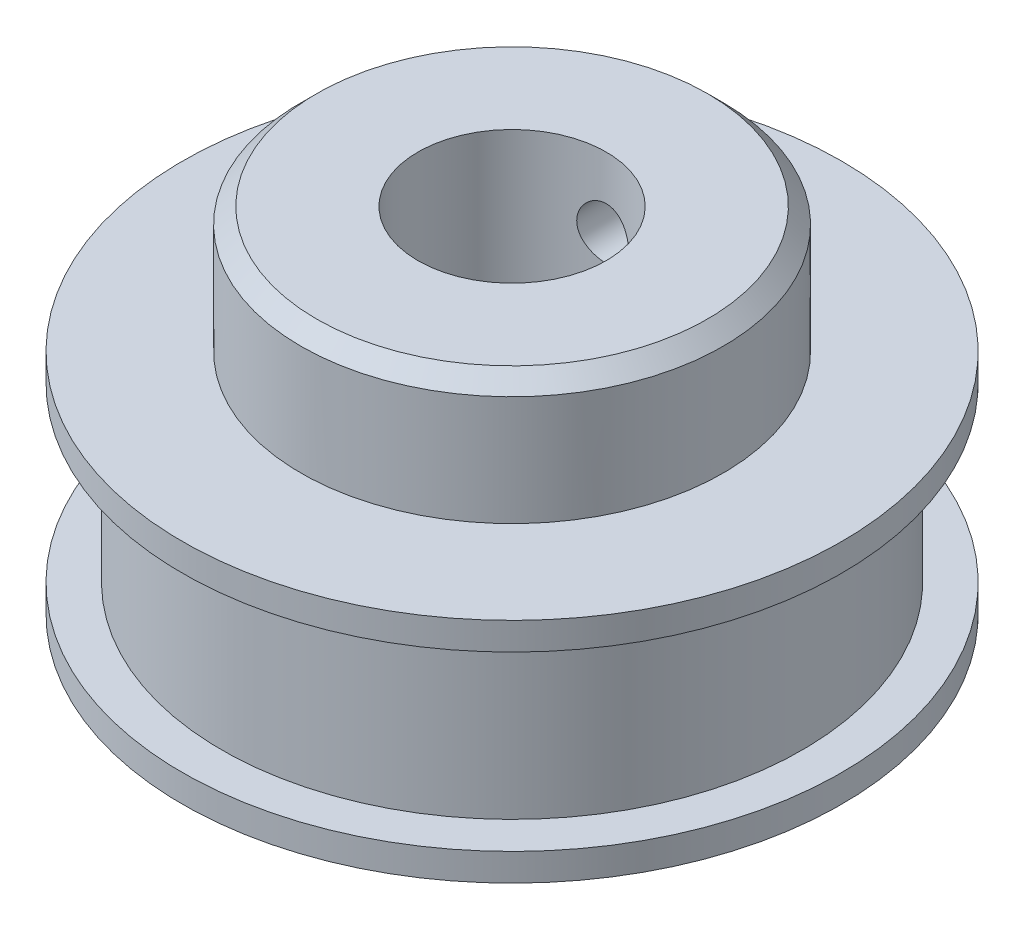
SolidWorks part; units mm, degrees
ref_plane "Piano frontale" through (0, 0, 0) normal (0, 0, 1) x (1, 0, 0)
ref_plane "Piano superiore" through (0, 0, 0) normal (0, 1, 0) x (1, 0, 0)
ref_plane "Piano destro" through (0, 0, 0) normal (1, 0, 0) x (0, 0, -1)
sketch "Schizzo1" plane through (0, 0, 0) normal (0, 0, 1) x (1, 0, 0)
  line L0 (0, 11.25) -> (13.45, 11.25)
  line L1 (13.45, 11.25) -> (13.45, 3.25)
  line L2 (13.45, 3.25) -> (21, 3.25)
  line L3 (21, 3.25) -> (21, 1.5)
  line L4 (21, 1.5) -> (18.5, 1.5)
  line L5 (18.5, 1.5) -> (18.5, -9.5)
  line L6 (18.5, -9.5) -> (21, -9.5)
  line L7 (21, -9.5) -> (21, -11.25)
  line L8 (21, -11.25) -> (0, -11.25)
  line L9 (0, -11.25) -> (0, 11.25)
  point P2 (21, 2.375)
  point P12 (0, 0)
  dimension "D1" = 13.45
  dimension "D2" = 21
  dimension "D3" = 18.5
  dimension "D4" = 11
  dimension "D5" = 22.5
  dimension "D6" = 8
ref_axis "Assi1" through (0, -12.375, 0) along (0, 1, 0)
revolve "Rivoluzione1" add sketch "Schizzo1" angle 360 about axis through (0, -12.375, 0) along (0, 1, 0)
chamfer "Smusso1" distance 1 angle 45 1 edges at (0, 11.25, -13.45)
sketch "Schizzo2" plane through (0, 11.25, 0) normal (0, 1, 0) x (1, 0, 0)
  circle A0 centre (0, 0) radius 6
  dimension "D1" = 12
extrude "Taglio-Estrusione1" cut sketch "Schizzo2" against normal through all
sketch "Schizzo3" plane through (0, 0, 0) normal (0, 0, 1) x (1, 0, 0)
  line L0 (13.45, 6.75) -> (-13.45, 6.75) construction
  line L1 (13.45, 3.25) -> (13.45, 10.25) construction
  line L2 (-13.45, 10.25) -> (-13.45, 3.25) construction
  circle A0 centre (0, 6.75) radius 1.65
  dimension "D1" = 3.3
extrude "Taglio-Estrusione2" cut sketch "Schizzo3" against normal through all
ref_plane "mezzeria_cinghia" through (0, -4, 0) normal (0, -1, 0) x (-1, 0, 0)
